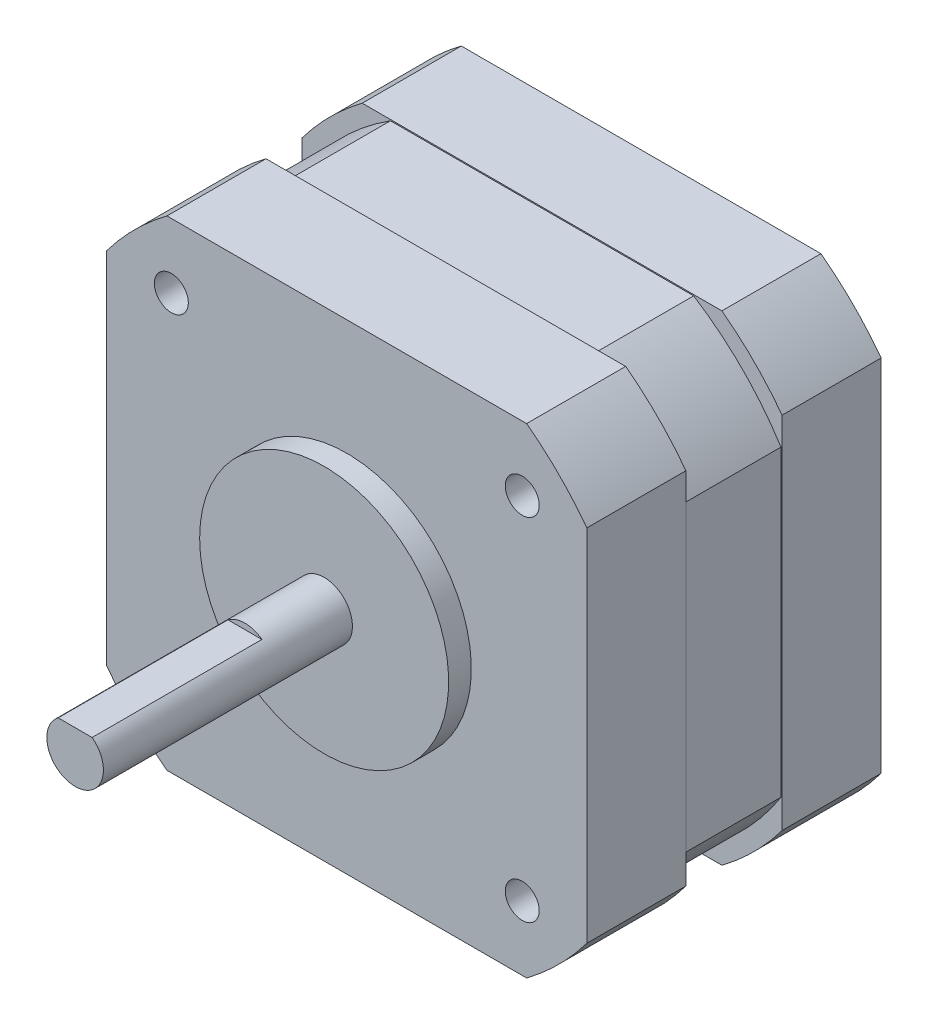
SolidWorks part; units mm, degrees
material "Plain Carbon Steel"
ref_plane "Front" through (0, 0, 0) normal (0, 0, 1) x (1, 0, 0)
ref_plane "Top" through (0, 0, 0) normal (0, 1, 0) x (1, 0, 0)
ref_plane "Right" through (0, 0, 0) normal (1, 0, 0) x (0, 0, -1)
sketch "Sketch1" plane through (0, 0, 0) normal (0, 0, 1) x (1, 0, 0)
  circle A0 centre (0, 0) radius 2.5
  dimension "D1" = 5
extrude "Boss-Extrude1" add sketch "Sketch1" along normal blind 24
sketch "Sketch2" plane through (0, 0, 0) normal (0, 0, -1) x (-1, 0, 0)
  circle A0 centre (0, 0) radius 11
  dimension "D1" = 22
extrude "Boss-Extrude2" add sketch "Sketch2" against normal blind 2
sketch "Sketch3" plane through (0, 0, 0) normal (0, 0, -1) x (-1, 0, 0)
  line L1 (21.209, -21.209) -> (-21.209, -21.209)
  line L2 (21.209, -21.209) -> (21.209, 21.209)
  line L3 (21.209, 21.209) -> (-21.209, 21.209)
  line L4 (-21.209, -21.209) -> (-21.209, 21.209)
  line L5 (21.209, -21.209) -> (-21.209, 21.209) construction
  line L6 (21.209, 21.209) -> (-21.209, -21.209) construction
  point P0 (0, 0)
  dimension "D1" = 42.418
extrude "Boss-Extrude3" add sketch "Sketch3" along normal blind 26
sketch "Sketch4" plane through (0, 0, -26) normal (0, 0, -1) x (-1, 0, 0)
  line L0 (-21.209, -15.888) -> (-21.209, -21.209)
  line L1 (15.888, -21.209) -> (21.209, -21.209)
  line L2 (21.209, 15.888) -> (21.209, 21.209)
  line L3 (-15.888, 21.209) -> (-21.209, 21.209)
  line L4 (-21.209, 21.209) -> (-21.209, -21.209)
  line L5 (-21.209, -21.209) -> (21.209, -21.209)
  line L6 (21.209, -21.209) -> (21.209, 21.209)
  line L7 (21.209, 21.209) -> (-21.209, 21.209)
  line L8 (-21.209, 21.209) -> (-21.209, 15.888)
  line L9 (-21.209, -21.209) -> (-15.888, -21.209)
  line L10 (21.209, -21.209) -> (21.209, -15.888)
  line L11 (21.209, 21.209) -> (15.888, 21.209)
  arc A0 (-21.209, -15.888) -> (-15.888, -21.209) centre (0, 0) ccw
  arc A1 (15.888, -21.209) -> (21.209, -15.888) centre (0, 0) ccw
  arc A2 (21.209, 15.888) -> (15.888, 21.209) centre (0, 0) ccw
  arc A3 (-15.888, 21.209) -> (-21.209, 15.888) centre (0, 0) ccw
  dimension "D2" = 26.5
  dimension "D1" = 0
extrude "Cut-Extrude1" cut sketch "Sketch4" against normal through all
hole_wizard "M3x0.5 Tapped Hole1" positions "Sketch6" profile "Sketch5" tap size "M3x0.5" standard "ANSI Metric"
sketch "Sketch6" plane through (0, 0, 0) normal (0, 0, 1) x (1, 0, 0)
  line L0 (-16.1632, 0) -> (0, 0) construction
  line L1 (0, 0) -> (0, 15.0764) construction
  point P0 (-15.5, 15.5)
  point P11 (-15.5, -15.5)
  point P12 (15.5, -15.5)
  point P13 (15.5, 15.5)
  dimension "D1" = 31
  dimension "D2" = 31
sketch "Sketch5" plane through (-15.5, 15.5, 0) normal (1, 0, 0) x (0, -1, 0)
  line L0 (0, 0) -> (0, 8.2511)
  line L1 (0, 8.2511) -> (1.25, 7.5)
  line L2 (1.25, 7.5) -> (1.25, 6)
  line L3 (1.25, 6) -> (1.5, 6)
  line L4 (1.5, 6) -> (1.5, 0)
  line L5 (1.5, 0) -> (0, 0)
  line L10 (0, 8.2511) -> (-1.25, 7.5) construction
  line L11 (0, -6.35) -> (0, 107.95) construction
  dimension "Tap Drill Dia." = 2.5
  dimension "Tap Drill Depth" = 7.5
  dimension "Thread Major Dia." = 3
  dimension "Thread Depth" = 6
  dimension "Drill Angle" = 118
sketch "Sketch7" plane through (0, 0, 24) normal (0, 0, 1) x (1, 0, 0)
  line L0 (-1.5, 2) -> (1.5, 2)
  circle A0 centre (0, 0) radius 2.5 construction
  circle A1 centre (0, 0) radius 2.5 construction
  arc A2 (1.5, 2) -> (-1.5, 2) centre (0, 0) ccw
  dimension "D1" = 4.5
extrude "Cut-Extrude2" cut sketch "Sketch7" against normal blind 15
ref_plane "Plane1" through (0, 0, -13) normal (0, 0, 1) x (1, 0, 0)
sketch "Sketch8" plane through (0, 0, -13) normal (0, 0, 1) x (1, 0, 0)
  line L0 (-13.3944, 21.109) -> (13.3944, 21.109)
  line L1 (-5.7152, 0) -> (0, 0) construction
  line L2 (0, 0) -> (0, 8.4579) construction
  line L3 (-15.888, 21.209) -> (15.888, 21.209) construction
  line L4 (-13.3944, -21.109) -> (13.3944, -21.109)
  line L5 (-21.109, 13.3944) -> (-21.109, -13.3944)
  line L6 (-21.209, -15.888) -> (-21.209, 15.888) construction
  line L7 (21.109, 13.3944) -> (21.109, -13.3944)
  line L12 (15.888, 21.209) -> (-15.888, 21.209)
  line L13 (-21.209, 15.888) -> (-21.209, -15.888)
  line L14 (-15.888, -21.209) -> (15.888, -21.209)
  line L15 (21.209, -15.888) -> (21.209, 15.888)
  line L16 (15.888, 21.209) -> (-15.888, 21.209)
  line L17 (-21.209, 15.888) -> (-21.209, -15.888)
  line L18 (-15.888, -21.209) -> (15.888, -21.209)
  line L19 (21.209, -15.888) -> (21.209, 15.888)
  arc A0 (-13.3944, 21.109) -> (-21.109, 13.3944) centre (0, 0) ccw
  arc A1 (-21.109, -13.3944) -> (-13.3944, -21.109) centre (0, 0) ccw
  arc A2 (21.109, 13.3944) -> (13.3944, 21.109) centre (0, 0) ccw
  arc A3 (13.3944, -21.109) -> (21.109, -13.3944) centre (0, 0) ccw
  arc A5 (-15.888, 21.209) -> (-21.209, 15.888) centre (0, 0) ccw
  arc A6 (-21.209, -15.888) -> (-15.888, -21.209) centre (0, 0) ccw
  arc A7 (15.888, -21.209) -> (21.209, -15.888) centre (0, 0) ccw
  arc A8 (21.209, 15.888) -> (15.888, 21.209) centre (0, 0) ccw
  arc A9 (-15.888, 21.209) -> (-21.209, 15.888) centre (0, 0) ccw
  arc A10 (-21.209, -15.888) -> (-15.888, -21.209) centre (0, 0) ccw
  arc A11 (15.888, -21.209) -> (21.209, -15.888) centre (0, 0) ccw
  arc A12 (21.209, 15.888) -> (15.888, 21.209) centre (0, 0) ccw
  dimension "D1" = 50
  dimension "D2" = 0.1
  dimension "D3" = 0.1
  dimension "D4" = 0
extrude "Cut-Extrude3" cut sketch "Sketch8" against normal offset from surface 8.75 and the other way offset from surface (4.25 mm away) 8.75 up to face at (0, 0, -26) other way up to face at (-14, 15.5, 0)
